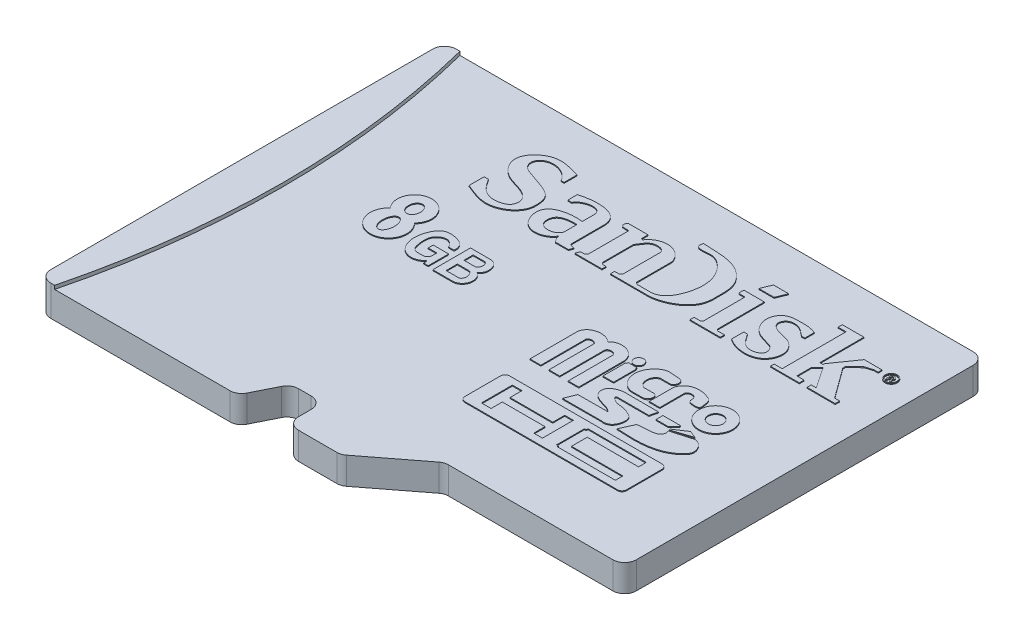
SolidWorks part; units mm, degrees
ref_plane "Front Plane" through (0, 0, 0) normal (0, 0, 1) x (1, 0, 0)
ref_plane "Top Plane" through (0, 0, 0) normal (0, 1, 0) x (1, 0, 0)
ref_plane "Right Plane" through (0, 0, 0) normal (1, 0, 0) x (0, 0, -1)
sketch "Sketch1" plane through (0, 0, 0) normal (0, 1, 0) x (1, 0, 0)
  line L1 (0, 0) -> (-15.24, 0)
  line L2 (0, 0) -> (0, 11.43)
  line L3 (0, 11.43) -> (-15.24, 11.43)
  line L4 (-15.24, 0) -> (-15.24, 11.43)
  dimension "D1" = 15.24
  dimension "D2" = 11.43
extrude "Boss-Extrude1" add sketch "Sketch1" along normal blind 0.762
sketch "Sketch2" plane through (0, 0.762, 0) normal (0, 1, 0) x (-1, 0, 0)
  line L0 (0, 0) -> (0, -1.27)
  line L1 (0, 0) -> (0, -11.43) construction
  line L2 (0, -1.27) -> (5.08, -1.27)
  line L3 (15.24, 0) -> (6.731, 0)
  line L4 (15.24, 0) -> (0, 0) construction
  line L5 (6.731, 0) -> (5.08, -1.27)
  line L6 (0, 0) -> (6.731, 0)
  line M1 (0, 0) -> (0, -11.43)
  line M4 (15.24, 0) -> (0, 0)
  dimension "D1" = 8.509
extrude "Cut-Extrude1" cut sketch "Sketch2" against normal blind 0.762 contours L5 L2 M4 M1
sketch "Sketch3" plane through (0, 0.762, 0) normal (0, 1, 0) x (-1, 0, 0)
  line L0 (6.731, 0) -> (8.255, 0)
  line L1 (15.24, 0) -> (6.731, 0) construction
  line L2 (8.255, 0) -> (8.255, -1.016)
  line L3 (8.255, -1.016) -> (9.144, -1.016)
  line L4 (15.24, 0) -> (9.652, 0)
  line L5 (9.652, 0) -> (9.144, -1.016)
  line L6 (8.255, 0) -> (9.652, 0)
  line M1 (15.24, 0) -> (6.731, 0)
  dimension "D1" = 1.016
extrude "Cut-Extrude2" cut sketch "Sketch3" against normal blind 0.762 contours L5 L2 L3 M1
sketch "Sketch4" plane through (0, 0.762, 0) normal (0, 1, 0) x (1, 0, 0)
  line L0 (-15.24, 0) -> (-14.8025, 0)
  line L1 (-15.24, 0) -> (-9.652, 0) construction
  line L2 (-15.24, 0) -> (-15.24, 11.43)
  line L3 (-15.24, 11.43) -> (-14.8025, 11.43)
  line L4 (0, 11.43) -> (-15.24, 11.43) construction
  arc A0 (-14.8025, 0) -> (-14.8025, 11.43) centre (-37.354, 5.715) ccw
extrude "Boss-Extrude2" add sketch "Sketch4" along normal blind 0.1016
fillet "Fillet1" radius 0.3302 10 edges at (-15.24, 0.4318, -11.43) (0, 0.381, -11.43) (0, 0.381, -1.27) (-15.24, 0.4318, 0) (-9.652, 0.381, 0) (-6.731, 0.381, 0) (-8.255, 0.381, -1.016) (-8.255, 0.381, 0) (-9.144, 0.381, -1.016) (-5.08, 0.381, -1.27)
sketch "Sketch5" plane through (0, 0, 0) normal (0, -1, 0) x (1, 0, 0)
  line L0 (0, -1.6002) -> (0, -11.0998) construction
  line L1 (-3.937, -10.668) -> (-1.016, -10.668)
  line L2 (-3.937, -10.668) -> (-3.937, -9.779)
  line L3 (-0.3302, -1.27) -> (-4.9677, -1.27) construction
  line L4 (-1.016, -10.668) -> (-1.016, -9.779)
  line L5 (-0.3302, -11.43) -> (-14.9098, -11.43) construction
  line L6 (-1.016, -3.81) -> (-1.016, -2.921)
  line L7 (-3.937, -2.667) -> (-1.016, -2.667)
  line L9 (-1.016, -8.382) -> (-3.937, -8.382)
  line L10 (-3.937, -10.668) -> (-1.016, -10.668)
  line L11 (-3.937, -10.668) -> (-3.937, -9.779)
  line L12 (-3.937, -9.525) -> (-3.937, -8.636)
  line L13 (-1.016, -10.668) -> (-1.016, -9.779)
  line L14 (-1.016, -8.636) -> (-3.937, -8.636)
  line L15 (-3.937, -8.382) -> (-3.937, -7.493)
  line L16 (-3.937, -7.493) -> (-1.016, -7.493)
  line L18 (-3.937, -7.239) -> (-1.016, -7.239)
  line L19 (-3.937, -7.239) -> (-3.937, -6.35)
  line L20 (-3.937, -6.35) -> (-1.016, -6.35)
  line L21 (-1.016, -7.239) -> (-1.016, -6.35)
  line L22 (-3.937, -6.096) -> (-1.016, -6.096)
  line L23 (-3.937, -6.096) -> (-3.937, -5.207)
  line L24 (-3.937, -5.207) -> (-1.016, -5.207)
  line L26 (-3.937, -4.953) -> (-1.016, -4.953)
  line L27 (-3.937, -4.953) -> (-3.937, -4.064)
  line L28 (-3.937, -4.064) -> (-1.016, -4.064)
  line L29 (-1.016, -4.953) -> (-1.016, -4.064)
  line L30 (-3.937, -3.81) -> (-1.016, -3.81)
  line L31 (-3.937, -3.81) -> (-3.937, -2.921)
  line L32 (-3.937, -2.921) -> (-1.016, -2.921)
  line L33 (-1.016, -3.81) -> (-1.016, -2.921)
  line L34 (-3.937, -2.667) -> (-1.016, -2.667)
  line L35 (-3.937, -2.667) -> (-3.937, -1.778)
  line L36 (-1.016, -9.525) -> (-1.016, -8.636)
  line L37 (-3.937, -1.778) -> (-1.016, -1.778)
  line L38 (-3.937, -9.525) -> (-1.016, -9.525)
  line L39 (-1.016, -9.779) -> (-3.937, -9.779)
  line L40 (-3.937, -9.779) -> (-3.937, -10.668)
  line L42 (-1.016, -7.239) -> (-1.016, -6.35)
  line L43 (-1.016, -4.953) -> (-1.016, -4.064)
  line L44 (-1.016, -2.667) -> (-1.016, -1.778)
  line L45 (-3.937, -3.81) -> (-3.937, -2.921)
  line L46 (-3.937, -4.953) -> (-3.937, -4.064)
  line L47 (-3.937, -6.096) -> (-3.937, -5.207)
  line L48 (-3.937, -7.239) -> (-3.937, -6.35)
  line L49 (-3.937, -8.382) -> (-3.937, -7.493)
  line L50 (-1.016, -8.382) -> (-0.508, -8.382)
  line L52 (-1.016, -7.493) -> (-0.508, -7.493)
  line L53 (-0.508, -8.382) -> (-0.508, -7.493)
  line L54 (-1.016, -6.096) -> (-0.508, -6.096)
  line L56 (-1.016, -5.207) -> (-0.508, -5.207)
  line L57 (-0.508, -6.096) -> (-0.508, -5.207)
  dimension "D1" = 1.016
  dimension "D2" = 2.921
  dimension "D3" = 0.889
  dimension "D4" = 0.762
  dimension "D5" = 0.508
  dimension "D6" = 0.254
  dimension "D7" = 0.254
  dimension "D8" = 0.254
  dimension "D9" = 0.254
  dimension "D10" = 0.254
  dimension "D11" = 0.254
  dimension "D12" = 0.254
  dimension "D13" = 0.889
  dimension "D14" = 0.889
  dimension "D15" = 0.889
  dimension "D16" = 0.889
  dimension "D17" = 0.889
  dimension "D18" = 0.889
  dimension "D19" = 0.889
  dimension "D20" = 0.508
  dimension "D21" = 0.508
  dimension "D22" = 0.762
extrude "Boss-Extrude3" add sketch "Sketch5" along normal blind 0.0254 contours L4 L39 L2 L1 | L12 L38 L36 L14 | L50 L53 L52 L16 L15 L9 | L18 L21 L20 L19 | L54 L57 L56 L24 L23 L22 | L26 L29 L28 L27 | L32 L31 L30 L6 | L7 L44 L37 L35
sketch "Sketch7" plane through (0, 0.762, 0) normal (0, 1, 0) x (1, 0, 0)
  line L0 (-6.2513, 4.2776) -> (-1.9489, 4.2776)
  line L1 (-6.3783, 3.1467) -> (-6.3783, 4.1506)
  line L2 (-1.8219, 4.1506) -> (-1.8219, 3.1467)
  line L3 (-6.2513, 3.0197) -> (-1.9489, 3.0197)
  line L4 (-3.8575, 3.2602) -> (-3.8575, 3.2204)
  line L5 (-5.9875, 4.0935) -> (-5.7163, 4.0935)
  line L6 (-5.9875, 4.0935) -> (-5.9875, 3.2204)
  line L7 (-5.9875, 3.2204) -> (-5.7163, 3.2204)
  line L8 (-5.7163, 4.0935) -> (-5.7163, 3.7562)
  line L9 (-5.7163, 3.7562) -> (-4.5124, 3.7562)
  line L10 (-4.6522, 6.238) -> (-4.6309, 6.238)
  line L11 (-5.7163, 3.5379) -> (-4.5124, 3.5379)
  line L12 (-6.3783, 4.9813) -> (-6.0723, 4.9813)
  line L13 (-4.5124, 4.0935) -> (-4.2676, 4.0935)
  line L14 (-4.5124, 4.0935) -> (-4.5124, 3.7562)
  line L15 (-4.5124, 3.2204) -> (-4.2676, 3.2204)
  line L16 (-4.2676, 4.0935) -> (-4.2676, 3.2204)
  line L17 (-2.2105, 4.0935) -> (-3.6591, 4.0935)
  line L18 (-2.2105, 4.0935) -> (-2.2105, 3.8753)
  line L19 (-2.2105, 3.8753) -> (-3.6591, 3.8753)
  line L20 (-5.7163, 3.5379) -> (-5.7163, 3.2204)
  line L21 (-3.6591, 3.4321) -> (-2.2105, 3.4321)
  line L22 (-4.5124, 3.5379) -> (-4.5124, 3.2204)
  line L23 (-3.6591, 3.2204) -> (-2.2105, 3.2204)
  line L24 (-2.2105, 3.4321) -> (-2.2105, 3.2204)
  line L25 (-3.6591, 4.0935) -> (-3.8575, 4.0935)
  line L26 (-3.6591, 3.8753) -> (-3.6591, 3.4321)
  line L27 (-3.6591, 3.2204) -> (-3.8575, 3.2204)
  line L28 (-3.8575, 4.0935) -> (-3.8575, 4.0431)
  line L29 (-3.8575, 4.0431) -> (-3.9051, 4.0431)
  line L30 (-6.3783, 4.9813) -> (-6.3783, 6.2548)
  line L31 (-3.8575, 3.2602) -> (-3.9051, 3.2602)
  line L32 (-3.9051, 4.0431) -> (-3.9051, 3.2602)
  line L33 (-4.9334, 6.238) -> (-4.9015, 6.238)
  line L34 (-6.0723, 4.9813) -> (-6.0723, 6.2548)
  line L35 (-5.8445, 4.9813) -> (-5.5407, 4.9813)
  line L36 (-5.8445, 4.9813) -> (-5.8445, 6.2548)
  line L37 (-4.9334, 6.238) -> (-4.9334, 5.5907)
  line L38 (-5.5407, 4.9813) -> (-5.5407, 6.2548)
  line L39 (-5.3012, 4.9813) -> (-5.0032, 4.9813)
  line L40 (-5.3012, 4.9813) -> (-5.3012, 6.2548)
  line L41 (-4.9334, 5.5907) -> (-4.6309, 5.5907)
  line L42 (-5.0032, 4.9813) -> (-5.0032, 6.2548)
  line L43 (-4.6309, 6.238) -> (-4.6309, 5.5907)
  line L44 (-4.9015, 6.2752) -> (-4.6522, 6.2752)
  line L45 (-4.9015, 6.2752) -> (-4.9015, 6.238)
  line L46 (-3.4429, 4.503) -> (-3.2763, 4.8725)
  line L47 (-4.6522, 6.2752) -> (-4.6522, 6.238)
  line L48 (-3.6591, 5.6234) -> (-3.3604, 5.6234)
  line L49 (-3.6591, 5.6234) -> (-3.6591, 6.3117)
  line L50 (-3.7899, 5.887) -> (-4.0732, 5.887)
  line L51 (-3.3604, 5.6234) -> (-3.3604, 6.3117)
  line L52 (-2.6655, 5.1728) -> (-2.092, 5.3378)
  line L53 (-2.6655, 5.2122) -> (-2.1761, 5.3772)
  line L55 (-2.677, 5.2122) -> (-2.6875, 5.2432)
  line L56 (-2.6875, 5.2432) -> (-2.3382, 5.4727)
  line L57 (-2.677, 5.2122) -> (-2.6655, 5.2122)
  line L58 (-2.7913, 5.2776) -> (-2.6228, 5.446)
  line L59 (-3.1208, 5.4727) -> (-2.7913, 5.4727)
  line L60 (-3.1208, 5.4727) -> (-3.1208, 5.2776)
  line L61 (-3.1208, 5.2776) -> (-2.7913, 5.2776)
  line L62 (-3.7899, 6.3467) -> (-4.0732, 6.3467)
  line L63 (-2.6228, 5.446) -> (-2.6228, 5.4727)
  line L64 (-2.6228, 5.4727) -> (-2.7913, 5.4727)
  line L65 (-3.2704, 5.4978) -> (-3.3216, 5.2776)
  line L66 (-4.1638, 5.4978) -> (-3.2704, 5.4978)
  line L67 (-10.0881, 5.8227) -> (-10.0881, 6.3968)
  line L68 (-10.0881, 6.3968) -> (-10.5243, 6.3968)
  line L69 (-10.5243, 6.3968) -> (-10.5243, 6.2548)
  line L70 (-10.5243, 6.2548) -> (-10.2787, 6.2548)
  line L71 (-10.2787, 6.2548) -> (-10.2787, 6.1098)
  line L72 (-9.9272, 6.8514) -> (-9.9272, 5.7884)
  line L73 (-9.9272, 5.7884) -> (-9.4021, 5.7884)
  line L74 (-9.9272, 6.8514) -> (-9.4021, 6.8514)
  line L75 (-10.2876, 6.6264) -> (-10.2584, 6.5651)
  line L76 (-10.2346, 6.5651) -> (-10.1069, 6.5651)
  line L77 (-10.2488, 5.9178) -> (-10.2195, 5.9178)
  line L78 (-10.2195, 5.9178) -> (-10.2195, 5.8227)
  line L79 (-10.2195, 5.8227) -> (-10.0881, 5.8227)
  line L80 (-9.7193, 5.9558) -> (-9.7193, 6.2752)
  line L81 (-9.7193, 6.2752) -> (-9.3754, 6.2752)
  line L82 (-9.7193, 5.9558) -> (-9.3754, 5.9558)
  line L83 (-9.7193, 6.7193) -> (-9.7193, 6.4584)
  line L84 (-9.7193, 6.4584) -> (-9.4021, 6.4584)
  line L85 (-9.7193, 6.7193) -> (-9.4021, 6.7193)
  line L86 (-2.3382, 5.4727) -> (-2.1351, 5.391)
  line L87 (-10.2584, 6.5651) -> (-10.2346, 6.5651)
  line L88 (-2.1351, 5.391) -> (-2.1761, 5.3772)
  arc A0 (-1.8219, 4.1506) -> (-1.9489, 4.2776) centre (-1.9489, 4.1506) ccw
  arc A1 (-1.9489, 3.0197) -> (-1.8219, 3.1467) centre (-1.9489, 3.1467) ccw
  arc A2 (-6.3783, 4.1506) -> (-6.2513, 4.2776) centre (-6.2513, 4.1506) cw
  arc A3 (-6.3783, 3.1467) -> (-6.2513, 3.0197) centre (-6.2513, 3.1467) ccw
  circle A4 centre (-4.7768, 6.4476) radius 0.1393
  circle A5 centre (-2.2776, 6.1174) radius 0.2094
  circle A6 centre (-2.2776, 6.1174) radius 0.4789
  arc A7 (-12.0329, 6.6958) -> (-11.3272, 6.6745) centre (-11.6915, 6.3057) ccw
  arc A9 (-11.3272, 6.6745) -> (-12.0329, 6.6958) centre (-11.6699, 7.019) ccw
  ellipse E0 centre (-11.6915, 6.3057) end of major axis (-11.6915, 6.5964) minor radius 0.1663
  ellipse E1 centre (-11.6699, 7.019) end of major axis (-11.6699, 6.7946) minor radius 0.169
  spline S0 degree 3 poles (-6.0723, 6.2548) (-6.0258, 6.3355) (-5.8909, 6.3393) (-5.8445, 6.2548) knots 0 0 0 0 1 1 1 1
  spline S1 degree 3 poles (-5.5407, 6.2548) (-5.5017, 6.3537) (-5.347, 6.3394) (-5.3012, 6.2548) knots 0 0 0 0 1 1 1 1
  spline S2 degree 3 poles (-6.3783, 6.2548) (-6.3949, 6.4033) (-6.1819, 6.6622) (-5.8165, 6.6067) (-5.6938, 6.491) knots 0 0 0 0 0.433334 1 1 1 1
  spline S3 degree 3 poles (-5.6938, 6.491) (-5.5783, 6.6381) (-5.2046, 6.6513) (-5.0049, 6.3846) (-5.0032, 6.2548) knots 0 0 0 0 0.585629 1 1 1 1
  spline S4 degree 3 poles (-3.2763, 4.8725) (-3.1951, 4.9327) (-2.7091, 4.8379) (-2.639, 5.0807) (-2.6655, 5.1728) knots 0 0 0 0 0.752776 1 1 1 1
  spline S5 degree 3 poles (-2.092, 5.3378) (-1.9266, 5.3484) (-1.6989, 5.0586) (-1.9519, 4.7635) (-2.4602, 4.4414) (-3.0627, 4.4842) (-3.4429, 4.503) knots 0 0 0 0 0.217544 0.299739 0.470311 1 1 1 1
  spline S6 degree 3 poles (-3.3604, 6.3117) (-3.3476, 6.4214) (-3.0701, 6.4316) (-3.126, 6.1798) (-2.9521, 6.1548) (-2.7757, 6.1567) (-2.8052, 6.3782) (-2.8197, 6.5249) (-2.9609, 6.5543) knots 0 0 0 0 0.243555 0.369108 0.483304 0.637611 0.698919 1 1 1 1
  spline S7 degree 3 poles (-2.9609, 6.5543) (-3.2055, 6.6648) (-3.5747, 6.6273) (-3.6591, 6.3117) knots 0 0 0 0 1 1 1 1
  spline S8 degree 3 poles (-4.0732, 5.887) (-4.2775, 5.9641) (-4.2653, 6.2758) (-4.0732, 6.3467) knots 0 0 0 0 1 1 1 1
  spline S9 degree 3 poles (-3.7899, 6.3467) (-3.6965, 6.3496) (-3.6392, 6.5447) (-3.7917, 6.6097) (-3.9434, 6.6122) (-4.166, 6.6505) (-4.423, 6.4775) (-4.5881, 6.1745) (-4.4991, 5.8017) (-4.2572, 5.6124) (-4.0574, 5.6253) (-3.9274, 5.6242) (-3.7869, 5.6179) (-3.6795, 5.7386) (-3.6947, 5.8813) (-3.7899, 5.887) knots 0 0 0 0 0.096113 0.118936 0.169797 0.264009 0.353301 0.488502 0.61513 0.743913 0.779012 0.830598 0.89028 0.917396 1 1 1 1
  spline S10 degree 1 poles (-4.8328, 4.7837) (-4.9579, 4.4738) knots 0 0 1 1
  spline S11 degree 1 poles (-4.9579, 4.4738) (-3.8575, 4.4777) knots 0 0 1 1
  spline S12 degree 1 poles (-4.8328, 4.7837) (-3.9808, 4.7891) knots 0 0 1 1
  spline S13 degree 3 poles (-3.8575, 4.4777) (-3.6649, 4.441) (-3.5061, 4.6375) (-3.5206, 4.9469) (-3.687, 5.0404) (-3.8907, 5.1238) (-4.119, 5.0948) (-4.3013, 5.2834) (-4.1696, 5.2776) knots 0 0 0 0 0.302788 0.449484 0.525022 0.661723 0.875336 1 1 1 1
  spline S14 degree 1 poles (-4.1696, 5.2776) (-3.3216, 5.2776) knots 0 0 1 1
  spline S15 degree 3 poles (-3.9808, 4.7891) (-4.0072, 4.8036) (-4.052, 4.8414) (-4.1573, 4.8872) (-4.0916, 4.8768) (-4.2163, 4.9061) knots 0 0 0 0 0.13693 0.181845 0.449154 0.449154 0.449154 0.449154
  spline S16 degree 3 poles (-4.2163, 4.9061) (-4.3337, 4.9434) (-4.5691, 4.9955) (-4.6553, 5.4129) (-4.2923, 5.5159) (-4.1638, 5.4978) knots 0 0 0 0 0.366225 0.53472 1 1 1 1
  spline S17 degree 3 poles (-10.2787, 6.1098) (-10.3222, 5.9816) (-10.4196, 5.9966) (-10.6928, 5.9895) (-10.7659, 6.1959) (-10.7958, 6.5884) (-10.5528, 6.7467) (-10.4206, 6.735) (-10.3747, 6.701) knots 0 0 0 0 0.171189 0.229954 0.387962 0.56983 0.72325 0.820267 0.820267 0.820267 0.820267
  spline S18 degree 2 poles (-10.1069, 6.5651) (-10.0796, 6.7483) (-10.2488, 6.8514) knots 0 0 0 1 1 1
  spline S19 degree 3 poles (-10.2488, 6.8514) (-10.384, 6.91) (-10.6964, 6.9781) (-10.8904, 6.698) (-10.9724, 6.4549) (-10.9871, 6.1404) (-10.8116, 5.8301) (-10.4888, 5.7566) (-10.3112, 5.845) (-10.2488, 5.9178) knots 0 0 0 0 0.227517 0.330562 0.43358 0.580561 0.751683 0.868589 1 1 1 1
  spline S20 degree 3 poles (-9.4021, 6.7193) (-9.3404, 6.7075) (-9.291, 6.5913) (-9.341, 6.4813) (-9.4021, 6.4584) knots 0 0 0 0 0.484272 1 1 1 1
  spline S21 degree 3 poles (-9.3754, 5.9558) (-9.32, 5.956) (-9.2301, 6.0905) (-9.3091, 6.2293) (-9.3754, 6.2752) knots 0 0 0 0 0.381651 1 1 1 1
  spline S22 degree 3 poles (-9.4021, 5.7884) (-9.244, 5.7775) (-9.0171, 5.9869) (-9.1158, 6.2882) (-9.2412, 6.3467) knots 0 0 0 0 0.510295 1 1 1 1
  spline S23 degree 3 poles (-9.2412, 6.3467) (-9.0289, 6.4622) (-9.1144, 6.8867) (-9.4021, 6.8514) knots 0 0 0 0 1 1 1 1
  spline S24 degree 3 poles (-10.3747, 6.701) (-10.3611, 6.69) (-10.3313, 6.6661) (-10.3029, 6.6403) (-10.2876, 6.6264) knots 0 0 0 0 0.458047 1 1 1 1
  dimension "D1" = 0.127
extrude "Boss-Extrude4" add sketch "Sketch7" along normal blind 0.0254
sketch "Sketch8" plane through (0, 0.762, 0) normal (0, 1, 0) x (1, 0, 0)
  line L0 (-11.3504, 8.7808) -> (-11.4731, 8.7808)
  line L1 (-11.4731, 8.7808) -> (-11.4731, 8.3563)
  line L2 (-10.2287, 10.1479) -> (-10.2083, 10.1432)
  line L3 (-10.2083, 10.1432) -> (-10.2083, 9.7737)
  line L4 (-10.2083, 9.7737) -> (-10.2936, 9.7737)
  line L5 (-8.1161, 9.5075) -> (-8.1161, 8.3563)
  line L6 (-7.7122, 9.2366) -> (-7.7122, 8.3563)
  line L7 (-7.1403, 8.3563) -> (-7.1403, 9.3658)
  line L8 (-6.7491, 9.3658) -> (-6.7491, 8.3563)
  line L9 (-6.7491, 8.3563) -> (-6.7027, 8.3099)
  line L10 (-6.7027, 8.3099) -> (-6.3465, 8.3099)
  line L11 (-7.3231, 8.3099) -> (-7.1964, 8.3099)
  line L12 (-7.1403, 8.3563) -> (-7.1867, 8.3099)
  line L13 (-7.1867, 8.3099) -> (-7.1964, 8.3099)
  line L14 (-7.3231, 8.3099) -> (-7.3231, 8.1934)
  line L15 (-7.3231, 8.1934) -> (-6.2739, 8.1934)
  line L16 (-7.7122, 8.3563) -> (-7.6658, 8.3099)
  line L17 (-7.6658, 8.3099) -> (-7.5614, 8.3099)
  line L18 (-7.5614, 8.3099) -> (-7.5614, 8.1934)
  line L19 (-7.5614, 8.1934) -> (-8.3253, 8.1934)
  line L20 (-8.3253, 8.1934) -> (-8.2844, 8.3099)
  line L21 (-8.2844, 8.3099) -> (-8.1615, 8.3099)
  line L22 (-8.1615, 8.3099) -> (-8.1161, 8.3563)
  line L23 (-7.6937, 9.4794) -> (-7.7435, 9.4794)
  line L24 (-7.7435, 9.4794) -> (-7.7435, 9.6318)
  line L25 (-7.7435, 9.6318) -> (-7.7435, 9.6753)
  line L26 (-7.7435, 9.6753) -> (-8.2844, 9.6753)
  line L27 (-8.1161, 9.5075) -> (-8.2288, 9.5075)
  line L28 (-8.6062, 8.3865) -> (-8.6062, 9.3213)
  line L29 (-9.7234, 9.659) -> (-9.7234, 9.3928)
  line L30 (-9.7234, 9.3928) -> (-9.61, 9.3928)
  line L31 (-8.9977, 9.0703) -> (-8.9977, 9.3807)
  line L32 (-8.9977, 8.5617) -> (-8.9977, 8.9273)
  line L33 (-8.8708, 8.1934) -> (-8.5087, 8.1934)
  line L34 (-8.5087, 8.1934) -> (-8.4643, 8.3099)
  line L35 (-0.8757, 9.504) -> (-0.8757, 9.6753)
  line L36 (-0.8757, 9.504) -> (-0.8757, 9.4998)
  line L37 (-0.8757, 9.4998) -> (-0.8411, 9.4998)
  line L38 (-0.8411, 9.4998) -> (-0.8411, 9.5659)
  line L39 (-0.8411, 9.5659) -> (-0.7884, 9.5659)
  line L40 (-0.7884, 9.5659) -> (-0.7657, 9.4998)
  line L41 (-0.7657, 9.4998) -> (-0.7296, 9.4998)
  line L42 (-0.7296, 9.4998) -> (-0.762, 9.58)
  line L43 (-0.8103, 9.6611) -> (-0.8459, 9.6611)
  line L44 (-0.8459, 9.6611) -> (-0.8459, 9.5899)
  line L45 (-0.8459, 9.5899) -> (-0.8103, 9.5899)
  line L46 (-4.8577, 9.504) -> (-4.8577, 8.3563)
  line L47 (-4.8577, 8.3563) -> (-4.9041, 8.3099)
  line L48 (-4.9041, 8.3099) -> (-5.081, 8.3099)
  line L49 (-5.081, 8.3099) -> (-5.081, 8.1934)
  line L50 (-5.081, 8.1934) -> (-4.2228, 8.1934)
  line L51 (-4.2228, 8.1934) -> (-4.2228, 8.3099)
  line L52 (-4.2228, 8.3099) -> (-4.4208, 8.3099)
  line L53 (-4.4208, 8.3099) -> (-4.4632, 8.3523)
  line L54 (-4.4632, 8.3523) -> (-4.4632, 9.6753)
  line L55 (-4.4632, 9.6753) -> (-5.037, 9.6753)
  line L56 (-5.037, 9.6753) -> (-5.0447, 9.6318)
  line L57 (-5.0447, 9.6318) -> (-5.0447, 9.6048)
  line L58 (-5.0447, 9.6048) -> (-5.0447, 9.5899)
  line L59 (-5.0447, 9.5899) -> (-5.0447, 9.5659)
  line L60 (-5.0447, 9.5659) -> (-5.0409, 9.5548)
  line L61 (-5.0409, 9.5548) -> (-5.0306, 9.525)
  line L62 (-5.0306, 9.525) -> (-4.8605, 9.5222)
  line L63 (-4.8605, 9.5222) -> (-4.8577, 9.504)
  line L64 (-4.8605, 9.9503) -> (-4.7501, 10.2187)
  line L65 (-4.7501, 10.2187) -> (-4.3218, 10.2187)
  line L66 (-4.3218, 10.2187) -> (-4.442, 9.9264)
  line L67 (-4.442, 9.9264) -> (-4.8689, 9.9264)
  line L68 (-4.022, 8.6537) -> (-4.022, 8.3099)
  line L70 (-4.8689, 9.9264) -> (-4.8605, 9.9503)
  line L72 (-4.022, 8.6537) -> (-3.918, 8.6537)
  line L73 (-3.0132, 9.3658) -> (-3.0132, 9.6318)
  line L74 (-3.0132, 9.6318) -> (-3.0132, 9.3658)
  line L75 (-3.0132, 9.3658) -> (-3.0132, 9.3696)
  line L76 (-3.0132, 9.3658) -> (-3.1036, 9.3658)
  line L77 (-2.5842, 10.0995) -> (-2.5842, 8.2968)
  line L78 (-2.2004, 8.3289) -> (-2.2004, 8.7334)
  line L79 (-2.2004, 10.2187) -> (-2.8099, 10.2187)
  line L80 (-2.8099, 10.2187) -> (-2.8099, 10.0995)
  line L81 (-2.8099, 10.0995) -> (-2.5842, 10.0995)
  line L82 (-2.2004, 8.9765) -> (-2.1091, 8.9765)
  line L83 (-2.1091, 8.9765) -> (-2.1091, 9.0158)
  line L84 (-2.1091, 9.0158) -> (-1.6475, 9.6753)
  line L85 (-1.6475, 9.6753) -> (-1.1458, 9.6753)
  line L86 (-1.1458, 9.6753) -> (-1.1458, 9.5659)
  line L87 (-1.1458, 9.5659) -> (-1.2628, 9.5659)
  line L88 (-1.2628, 9.5659) -> (-1.477, 9.4998)
  line L89 (-2.2004, 8.7334) -> (-2.0347, 8.899)
  line L90 (-2.0347, 8.899) -> (-1.6475, 8.3289)
  line L91 (-1.6475, 8.3289) -> (-1.6475, 8.3099)
  line L92 (-1.6475, 8.3099) -> (-1.7769, 8.3099)
  line L93 (-1.7769, 8.3099) -> (-1.7769, 8.1934)
  line L94 (-1.7769, 8.1934) -> (-0.9846, 8.1934)
  line L95 (-0.9846, 8.1934) -> (-0.9846, 8.3194)
  line L96 (-0.9846, 8.3194) -> (-1.1262, 8.3194)
  line L97 (-1.1262, 8.3194) -> (-1.7435, 9.1664)
  line L98 (-1.7435, 9.1664) -> (-1.7435, 9.2366)
  line L99 (-1.7435, 9.2366) -> (-1.477, 9.4998)
  line L100 (-2.2004, 8.9765) -> (-2.2004, 10.2187)
  line L101 (-2.5842, 8.2968) -> (-2.8099, 8.2968)
  line L102 (-2.8099, 8.2968) -> (-2.8099, 8.1934)
  line L103 (-2.8099, 8.1934) -> (-1.9969, 8.1934)
  line L104 (-1.9969, 8.1934) -> (-1.9969, 8.3289)
  line L105 (-1.9969, 8.3289) -> (-2.2004, 8.3289)
  circle A0 centre (-0.8103, 9.598) radius 0.1718
  circle A1 centre (-0.8103, 9.598) radius 0.1502
  arc A2 (-0.8103, 9.5899) -> (-0.8103, 9.6611) centre (-0.8103, 9.6255) ccw
  spline S0 degree 3 poles (-11.3504, 8.7808) (-11.2631, 8.6408) (-11.0622, 8.3505) (-10.6545, 8.3458) (-10.3955, 8.4653) (-10.337, 8.6915) (-10.4513, 8.8628) (-10.7183, 9.0393) (-11.1861, 9.0748) (-11.6636, 9.7264) (-11.115, 10.253) (-10.6132, 10.2585) (-10.3672, 10.1799) (-10.2287, 10.1479) knots 0 0 0 0 0.119927 0.211939 0.253863 0.306778 0.345951 0.387535 0.522259 0.656982 0.829585 0.899642 1 1 1 1
  spline S1 degree 3 poles (-10.2936, 9.7737) (-10.367, 9.9032) (-10.5746, 10.0649) (-10.9043, 10.0879) (-11.1332, 9.9699) (-11.1941, 9.7442) (-11.0573, 9.5744) (-10.8477, 9.5025) (-10.6055, 9.4156) (-10.3358, 9.3292) (-10.1004, 9.1778) (-10.0425, 8.904) (-10.0523, 8.455) (-10.7445, 8.0214) (-11.2415, 8.266) (-11.4731, 8.3563) knots 0 0 0 0 0.099105 0.164709 0.211337 0.261499 0.296298 0.346607 0.407752 0.468696 0.539665 0.577748 0.650875 0.829654 1 1 1 1
  spline S2 degree 3 poles (-7.7122, 9.2366) (-7.65, 9.3232) (-7.5634, 9.5216) (-7.2753, 9.5649) (-7.127, 9.4816) (-7.1403, 9.3658) knots 0 0 0 0 0.432808 0.67871 1 1 1 1
  spline S3 degree 3 poles (-6.7491, 9.3658) (-6.7972, 9.5189) (-7.113, 9.8345) (-7.5706, 9.6718) (-7.6937, 9.4794) knots 0 0 0 0 0.415672 1 1 1 1
  spline S4 degree 3 poles (-8.2844, 9.6753) (-8.3267, 9.6718) (-8.338, 9.6134) (-8.3417, 9.5503) (-8.303, 9.5048) (-8.2531, 9.5144) (-8.2288, 9.5075) knots 0 0 0 0 0.374563 0.583509 0.663143 1 1 1 1
  spline S5 degree 3 poles (-6.3465, 8.3099) (-6.0281, 8.295) (-5.7414, 8.7876) (-5.6875, 9.5109) (-6.02, 9.9637) (-6.4364, 10.1355) (-6.8302, 9.9682) (-6.7491, 10.2443) knots 0 0 0 0 0.290209 0.518144 0.74116 0.80808 1 1 1 1
  spline S6 degree 3 poles (-6.7491, 10.2443) (-6.4064, 10.2194) (-5.7989, 10.2686) (-5.2685, 9.7068) (-5.2615, 9.2178) (-5.2484, 8.5135) (-5.9362, 8.1927) (-6.2739, 8.1934) knots 0 0 0 0 0.290579 0.450128 0.558006 0.68222 1 1 1 1
  spline S7 degree 3 poles (-8.6062, 9.3213) (-8.6302, 9.8627) (-9.426, 9.7525) (-9.7234, 9.659) knots 0 0 0 0 1 1 1 1
  spline S8 degree 2 poles (-8.8708, 8.1934) (-8.9611, 8.2917) (-8.9758, 8.3865) knots 0 0 0 0.331539 0.331539 0.331539
  spline S9 degree 3 poles (-8.9977, 9.3807) (-8.9738, 9.7244) (-9.5273, 9.6) (-9.61, 9.3928) knots 0 0 0 0 1 1 1 1
  spline S10 degree 3 poles (-8.9758, 8.3865) (-9.0991, 8.1672) (-9.7318, 7.9926) (-10.0624, 9.0596) (-9.1989, 9.1091) (-8.9977, 9.0703) knots 0 0 0 0 0.332329 0.599426 1 1 1 1
  spline S11 degree 3 poles (-8.9977, 8.9273) (-9.1393, 8.9265) (-9.5422, 8.9329) (-9.5589, 8.3044) (-9.0515, 8.3667) (-8.9977, 8.5617) knots 0 0 0 0 0.378427 0.595168 1 1 1 1
  spline S12 degree 2 poles (-8.4643, 8.3099) (-8.6164, 8.3295) (-8.6062, 8.3865) knots 0 0 0 0.687711 0.687711 0.687711
  spline S13 degree 3 poles (-0.8757, 9.6753) (-0.8199, 9.7394) (-0.6775, 9.6479) (-0.762, 9.58) knots 0 0 0 0 1 1 1 1
  spline S14 degree 3 poles (-3.918, 8.6537) (-3.8448, 8.5542) (-3.7222, 8.3146) (-3.3945, 8.2867) (-3.1589, 8.4414) (-3.2581, 8.6769) (-3.4322, 8.7129) (-3.5518, 8.7614) (-3.9022, 8.8552) (-4.1027, 9.2082) (-3.9713, 9.4794) knots 0 0 0 0 0.171536 0.302151 0.380829 0.486858 0.532299 0.607554 0.653711 1 1 1 1
  spline S15 degree 3 poles (-3.9713, 9.4794) (-3.8768, 9.6804) (-3.5086, 9.7071) (-3.1687, 9.698) (-3.0132, 9.6318) knots 0 0 0 0 0.528193 1 1 1 1
  spline S16 degree 3 poles (-3.1036, 9.3658) (-3.1959, 9.434) (-3.3473, 9.5953) (-3.6995, 9.5809) (-3.7985, 9.2988) (-3.5338, 9.1149) (-3.1957, 9.1203) (-2.8444, 8.7641) (-3.097, 8.0271) (-3.7882, 8.1388) (-4.022, 8.3099) knots 0 0 0 0 0.102364 0.197564 0.250005 0.324553 0.434792 0.557847 0.704556 1 1 1 1
extrude "Boss-Extrude6" add sketch "Sketch8" along normal blind 0.0254 contours A0 A1 | S13 L35 L36 L37 L38 L39 L40 L41 L42 A2 L45 L44 L43 | L104 L105 L78 L89 L90 L91 L92 L93 L94 L95 L96 L97 L98 L99 L88 L87 L86 L85 L84 L83 L82 L100 L79 L80 L81 L77 L101 L102 L103 | S16 L76 L73 L74 S15 S14 L72 L68 | L62 L63 L46 L47 L48 L49 L50 L51 L52 L53 L54 L55 L56 L57 L58 L59 L60 L61 | S6 S5 L10 L9 L8 S3 L23 L24 L25 L26 S4 L27 L5 L22 L21 L20 L19 L18 L17 L16 L6 S2 L7 L12 L13 L11 L14 L15 | L34 S12 L28 S7 L29 L30 S9 L31 S10 S8 L33 S11 L32 | S1 L4 L3 L2 S0 L0 L1 | L70 L67 L66 L65 L64
